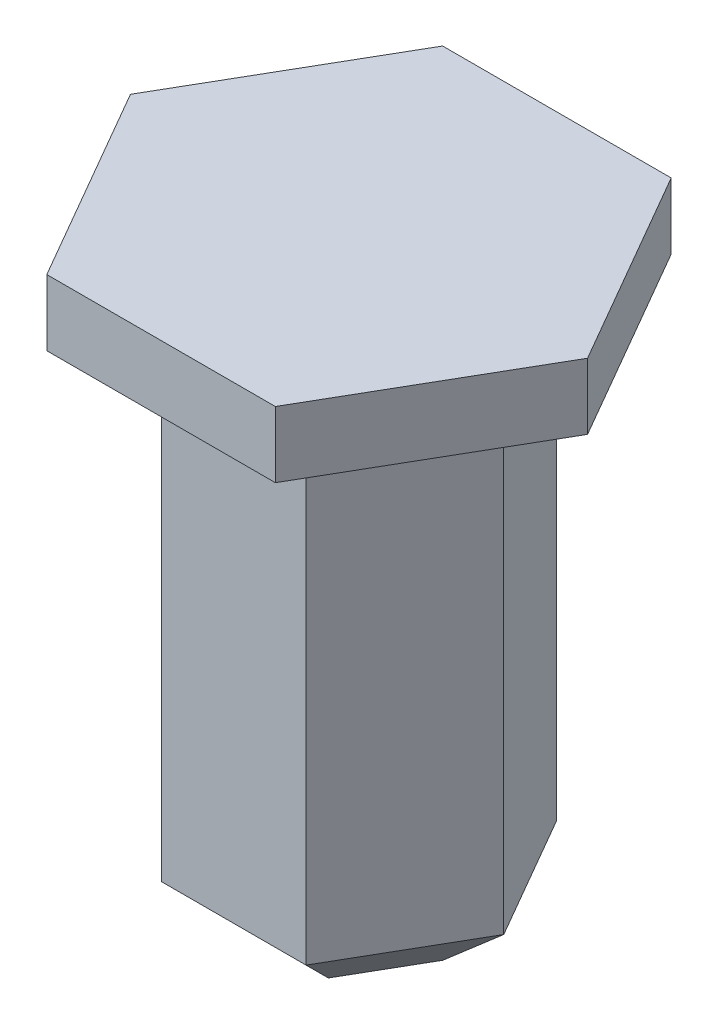
SolidWorks part; units mm, degrees
ref_plane "Front Plane" through (0, 0, 0) normal (0, 0, 1) x (1, 0, 0)
ref_plane "Top Plane" through (0, 0, 0) normal (0, 1, 0) x (1, 0, 0)
ref_plane "Right Plane" through (0, 0, 0) normal (1, 0, 0) x (0, 0, -1)
sketch "Sketch1" plane through (0, 0, 0) normal (0, 1, 0) x (1, 0, 0)
  line L1 (2.1939, 0) -> (1.097, 1.9)
  line L2 (1.097, 1.9) -> (-1.097, 1.9)
  line L3 (-1.097, 1.9) -> (-2.1939, 0)
  line L4 (-2.1939, 0) -> (-1.097, -1.9)
  line L5 (-1.097, -1.9) -> (1.097, -1.9)
  line L6 (1.097, -1.9) -> (2.1939, 0)
  circle A0 centre (0, 0) radius 1.9 construction
  dimension "D1" = 3.8
extrude "Boss-Extrude1" add sketch "Sketch1" along normal blind 8 contours L3 L4 L5 L6 L1 L2
sketch "Sketch2" plane through (0, 8, 0) normal (0, 1, 0) x (1, 0, 0)
  line L1 (3.4641, 0) -> (1.7321, 3)
  line L2 (1.7321, 3) -> (-1.7321, 3)
  line L3 (-1.7321, 3) -> (-3.4641, 0)
  line L4 (-3.4641, 0) -> (-1.7321, -3)
  line L5 (-1.7321, -3) -> (1.7321, -3)
  line L6 (1.7321, -3) -> (3.4641, 0)
  circle A0 centre (0, 0) radius 3 construction
  dimension "D1" = 6
extrude "Boss-Extrude2" add sketch "Sketch2" along normal blind 1
chamfer "Chamfer1" distance 0.8 angle 45 6 edges at (-1.6454, 0, -0.95) (-1.6454, 0, 0.95) (0, 0, 1.9) (1.6454, 0, 0.95) (1.6454, 0, -0.95) (0, 0, -1.9)
